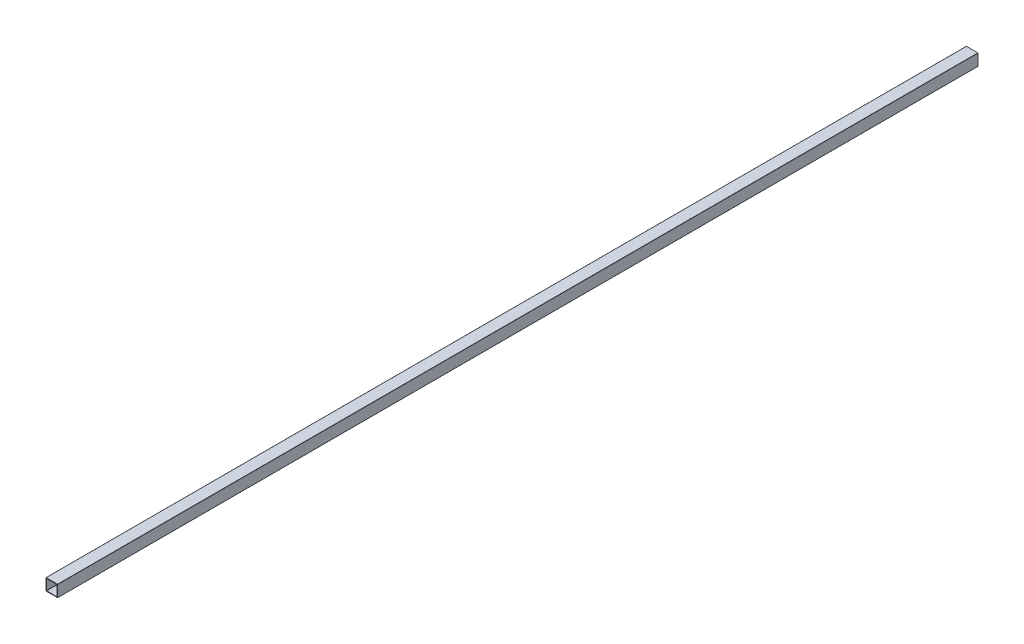
SolidWorks part; units mm, degrees
material "AISI 1035 Acero (SS)"
ref_plane "Alzado" through (0, 0, 0) normal (0, 0, 1) x (1, 0, 0)
ref_plane "Planta" through (0, 0, 0) normal (0, 1, 0) x (1, 0, 0)
ref_plane "Vista lateral" through (0, 0, 0) normal (1, 0, 0) x (0, 0, -1)
sketch "Croquis1" plane through (0, 0, 0) normal (0, 0, 1) x (1, 0, 0)
  line L0 (-34.6, -34.6) -> (-34.6, 34.6)
  line L1 (-38.1, -38.1) -> (38.1, -38.1)
  line L2 (-38.1, -38.1) -> (-38.1, 38.1)
  line L3 (-38.1, 38.1) -> (38.1, 38.1)
  line L4 (38.1, -38.1) -> (38.1, 38.1)
  line L5 (-38.1, -38.1) -> (38.1, 38.1) construction
  line L6 (-38.1, 38.1) -> (38.1, -38.1) construction
  line L7 (-34.6, 34.6) -> (34.6, 34.6)
  line L8 (34.6, -34.6) -> (34.6, 34.6)
  line L9 (-34.6, -34.6) -> (34.6, -34.6)
  point P0 (0, 0)
  dimension "D1" = 76.2
  dimension "D3" = 3.5
extrude "Saliente-Extruir1" add sketch "Croquis1" against normal blind 6000
fillet "Redondeo1" radius 1 8 edges at (-34.6, 34.6, -3000) (34.6, 34.6, -3000) (34.6, -34.6, -3000) (-38.1, -38.1, -3000) (-38.1, 38.1, -3000) (-34.6, -34.6, -3000) (38.1, -38.1, -3000) (38.1, 38.1, -3000)
